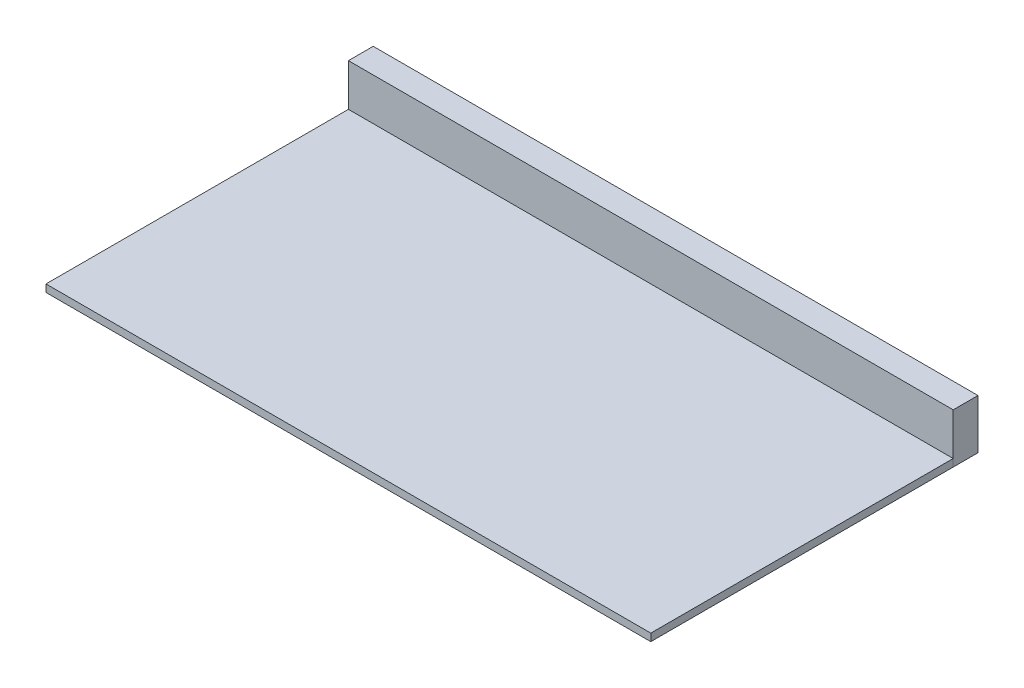
SolidWorks part; units mm, degrees
ref_plane "Front Plane" through (0, 0, 0) normal (0, 0, 1) x (1, 0, 0)
ref_plane "Top Plane" through (0, 0, 0) normal (0, 1, 0) x (1, 0, 0)
ref_plane "Right Plane" through (0, 0, 0) normal (1, 0, 0) x (0, 0, -1)
sketch "Sketch1" plane through (0, 0, 0) normal (0, 1, 0) x (1, 0, 0)
  line L1 (0, 0) -> (2438.4, 0)
  line L2 (0, 0) -> (0, 1219.2)
  line L3 (0, 1219.2) -> (2438.4, 1219.2)
  line L4 (2438.4, 0) -> (2438.4, 1219.2)
  dimension "D1" = 2438.4
  dimension "D2" = 1219.2
extrude "Boss-Extrude1" add sketch "Sketch1" along normal blind 30
sketch "Sketch2" plane through (0, 0, 0) normal (0, -1, 0) x (1, 0, 0)
  line L0 (2438.4, 0) -> (2438.4, -1219.2) construction
  line L1 (0, -1219.2) -> (2438.4, -1219.2)
  line L2 (0, -1219.2) -> (0, -1319.2)
  line L3 (0, -1319.2) -> (2438.4, -1319.2)
  line L4 (2438.4, -1219.2) -> (2438.4, -1319.2)
  dimension "D1" = 100
extrude "Boss-Extrude2" add sketch "Sketch2" against normal blind 200 separate body
